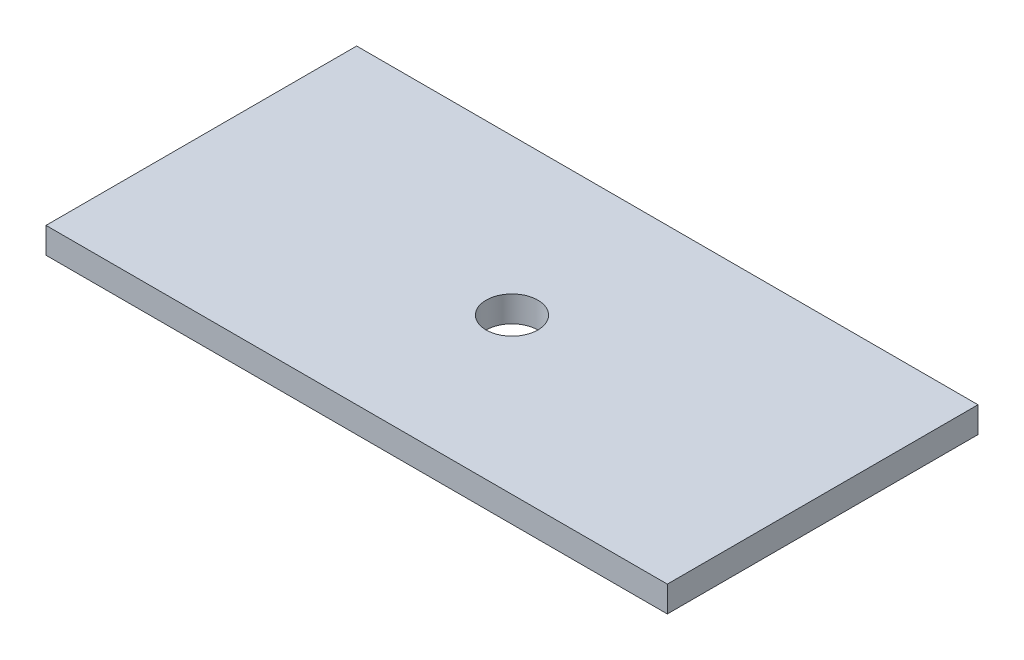
SolidWorks part; units mm, degrees
ref_plane "Front Plane" through (0, 0, 0) normal (0, 0, 1) x (1, 0, 0)
ref_plane "Top Plane" through (0, 0, 0) normal (0, 1, 0) x (1, 0, 0)
ref_plane "Right Plane" through (0, 0, 0) normal (1, 0, 0) x (0, 0, -1)
sketch "Sketch1" plane through (0, 0, 0) normal (0, 1, 0) x (1, 0, 0)
  line L1 (-76.2, -38.1) -> (76.2, -38.1)
  line L2 (-76.2, -38.1) -> (-76.2, 38.1)
  line L3 (-76.2, 38.1) -> (76.2, 38.1)
  line L4 (76.2, -38.1) -> (76.2, 38.1)
  line L5 (-76.2, -38.1) -> (76.2, 38.1) construction
  line L6 (-76.2, 38.1) -> (76.2, -38.1) construction
  circle A0 centre (0, 0) radius 6.35
  point P0 (0, 0)
  dimension "D3" = 12.7
  dimension "D1" = 152.4
  dimension "D2" = 76.2
extrude "Boss-Extrude1" add sketch "Sketch1" along normal blind 6.35
